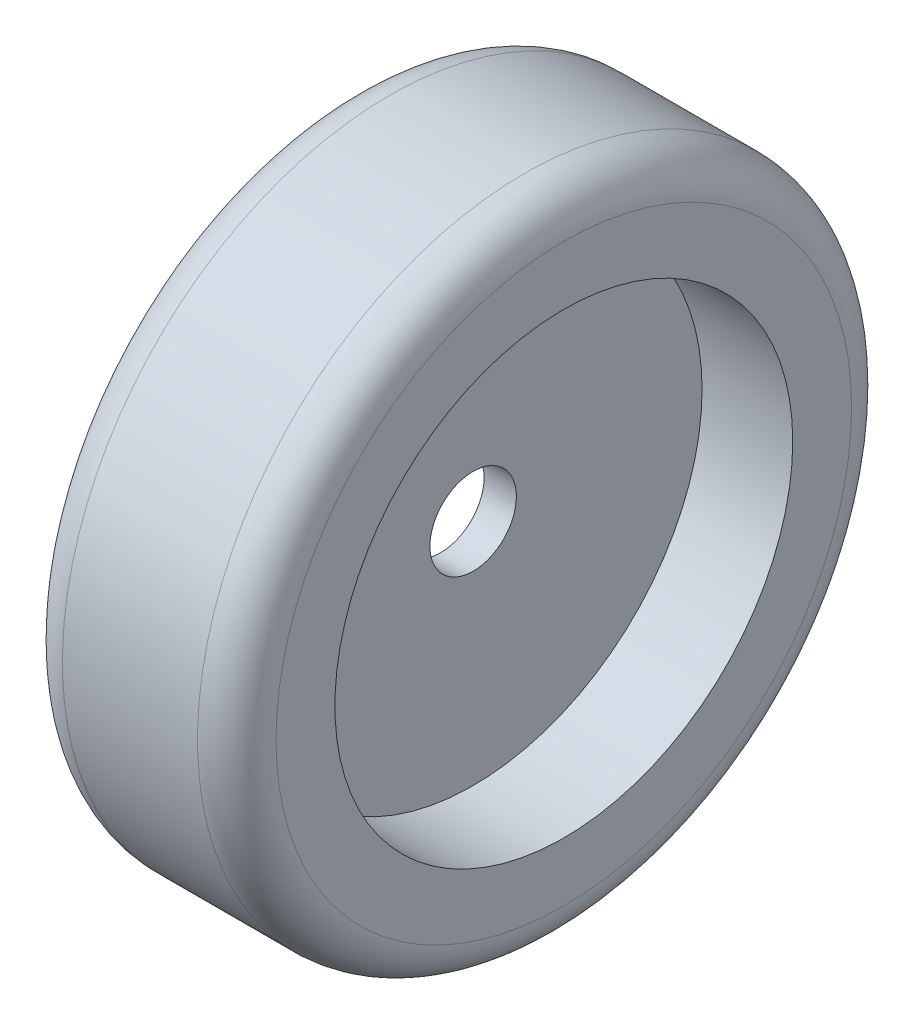
SolidWorks part; units mm, degrees
material "Silicon Rubber"
ref_plane "Front Plane" through (0, 0, 0) normal (0, 0, 1) x (1, 0, 0)
ref_plane "Top Plane" through (0, 0, 0) normal (0, 1, 0) x (1, 0, 0)
ref_plane "Right Plane" through (0, 0, 0) normal (1, 0, 0) x (0, 0, -1)
sketch "Sketch1" plane through (0, 0, 0) normal (1, 0, 0) x (0, 0, -1)
  circle A0 centre (0, 0) radius 127
  circle A1 centre (0, 0) radius 16.7894
  dimension "D1" = 254
  dimension "D2" = 33.5788
extrude "Boss-Extrude1" add sketch "Sketch1" along normal blind 82.9564
fillet "Fillet1" radius 15.24 2 edges at (82.9564, 0, -127) (0, 0, -127)
ref_plane "Plane1" through (0, 0, -127) normal (0, 0, -1) x (-1, 0, 0)
sketch "Sketch2" plane through (82.9564, 0, 0) normal (1, 0, 0) x (0, 0, -1)
  circle A0 centre (0, 0) radius 88.9
  circle A1 centre (0, 0) radius 16.7894
  circle A2 centre (0, 0) radius 16.7894 construction
  dimension "D1" = 177.8
extrude "Cut-Extrude1" cut sketch "Sketch2" against normal blind 35.2044
ref_plane "Plane2" through (41.4782, 0, 0) normal (-1, 0, 0) x (0, 0, 1)
mirror "Mirror1" about plane through (41.4782, 0, 0) normal (-1, 0, 0) of "Cut-Extrude1"
